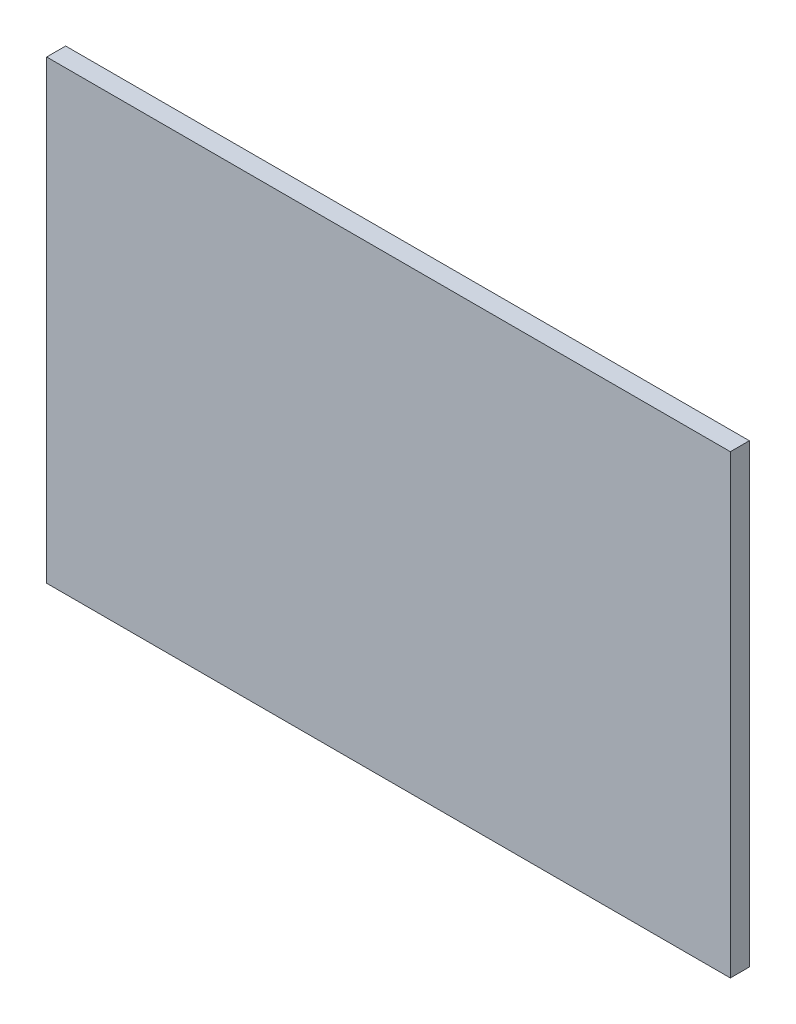
SolidWorks part; units mm, degrees
ref_plane "Front Plane" through (0, 0, 0) normal (0, 0, 1) x (1, 0, 0)
ref_plane "Top Plane" through (0, 0, 0) normal (0, 1, 0) x (1, 0, 0)
ref_plane "Right Plane" through (0, 0, 0) normal (1, 0, 0) x (0, 0, -1)
sketch "Sketch1" plane through (0, 0, 0) normal (0, 0, 1) x (1, 0, 0)
  line L1 (0, 0) -> (720, 0)
  line L2 (0, 0) -> (0, 480)
  line L3 (0, 480) -> (720, 480)
  line L4 (720, 0) -> (720, 480)
  dimension "D1" = 480
  dimension "D2" = 720
extrude "Boss-Extrude1" add sketch "Sketch1" along normal blind 20
